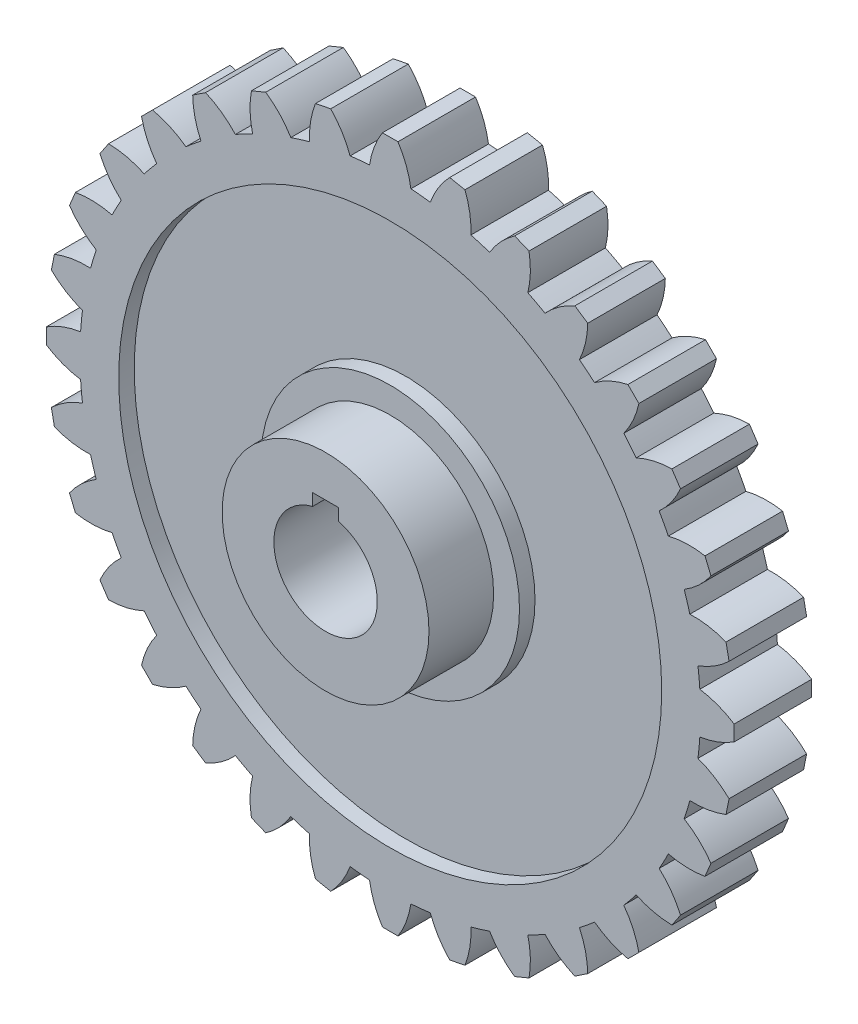
SolidWorks part; units mm, degrees
ref_plane "Front Plane" through (0, 0, 0) normal (0, 0, 1) x (1, 0, 0)
ref_plane "Top Plane" through (0, 0, 0) normal (0, 1, 0) x (1, 0, 0)
ref_plane "Right Plane" through (0, 0, 0) normal (1, 0, 0) x (0, 0, -1)
sketch "Sketch1" plane through (0, 0, 0) normal (0, 0, 1) x (1, 0, 0)
  circle A0 centre (0, 0) radius 60
  dimension "D1" = 120
extrude "Boss-Extrude1" add sketch "Sketch1" along normal mid plane 15
sketch "Sketch2" plane through (0, 0, 7.5) normal (0, 0, 1) x (1, 0, 0)
  line L0 (0, 0) -> (0, 66.5) construction
  line L1 (-1.5, 66.5) -> (1.5, 66.5)
  circle A0 centre (0, 0) radius 60 construction
  arc A1 (4, 59.8665) -> (-4, 59.8665) centre (0, 0) ccw
  arc A2 (-1.5, 66.5) -> (-4, 59.8665) centre (12.8082, 57.3198) ccw
  arc A3 (1.5, 66.5) -> (4, 59.8665) centre (-12.8082, 57.3198) cw
  point P7 (0, 66.5)
  dimension "D3" = 17
  dimension "D1" = 6.5
  dimension "D2" = 3
  dimension "D4" = 8
extrude "Boss-Extrude2" add sketch "Sketch2" against normal up to surface (15 mm away) up to face at (60, 0, -7.5)
pattern_circular "CirPattern1" count 32 over 360 about axis through (0, 0, 0) along (0, 0, 1) of "Boss-Extrude2"
sketch "Sketch3" plane through (0, 0, 0) normal (0, 0, 1) x (1, 0, 0)
  circle A0 centre (0, 0) radius 20
  dimension "D1" = 40
extrude "Boss-Extrude3" add sketch "Sketch3" along normal mid plane 40
sketch "Sketch4" plane through (0, 0, 20) normal (0, 0, 1) x (1, 0, 0)
  line L0 (0, 0) -> (0, 12) construction
  line L1 (-2.5, 12) -> (2.5, 12)
  line L2 (-2.5, 12) -> (-2.5, 9.6825)
  line L3 (2.5, 12) -> (2.5, 9.6825)
  arc A0 (-2.5, 9.6825) -> (2.5, 9.6825) centre (0, 0) ccw
  point P7 (0, 12)
  dimension "D1" = 20
  dimension "D2" = 5
  dimension "D3" = 12
extrude "Cut-Extrude1" cut sketch "Sketch4" against normal through all
sketch "Sketch5" plane through (0, 0, 0) normal (0, 0, 1) x (1, 0, 0)
  circle A1 centre (0, 0) radius 52.5
  circle A2 centre (0, 0) radius 25
  circle A3 centre (0, 0) radius 25
  dimension "D2" = 105
  dimension "D1" = 5
extrude "Cut-Extrude2" cut sketch "Sketch5" against normal blind 3 from surface at 7.5 starting at face at (20, 0, 7.5)
mirror "Mirror1" about plane through (0, 0, 0) normal (0, 0, 1) of "Cut-Extrude2"
